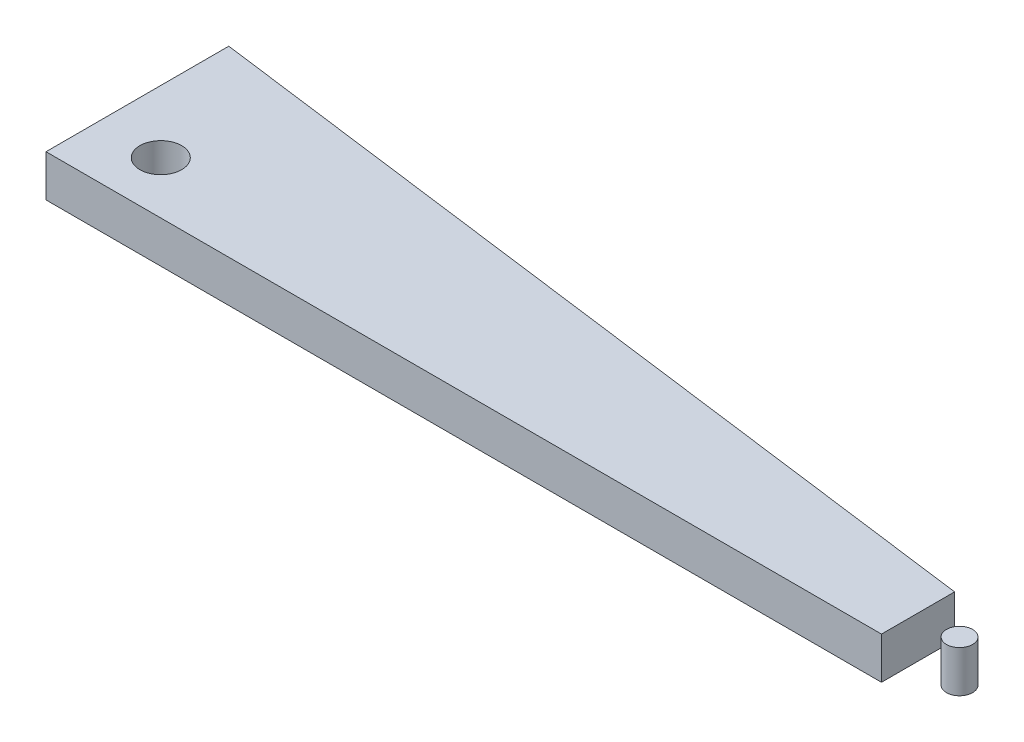
SolidWorks part; units mm, degrees
material "6061-T6 (SS)"
ref_plane "Front Plane" through (0, 0, 0) normal (0, 0, 1) x (1, 0, 0)
ref_plane "Top Plane" through (0, 0, 0) normal (0, 1, 0) x (1, 0, 0)
ref_plane "Right Plane" through (0, 0, 0) normal (1, 0, 0) x (0, 0, -1)
sketch "Sketch1" plane through (0, 0, 0) normal (0, 1, 0) x (1, 0, 0)
  line L0 (0, 0) -> (160, 0)
  line L5 (160, 0) -> (160, 14)
  line L6 (0, 0) -> (0, 35)
  line L7 (0, 35) -> (160, 14)
  circle A0 centre (11.9789, 10) radius 4
  circle A1 centre (167.9474, 7) radius 2.5
  dimension "D4" = 8
  dimension "D5" = 5
  dimension "D1" = 160
  dimension "D2" = 14
  dimension "D3" = 35
extrude "Boss-Extrude1" add sketch "Sketch1" along normal blind 8
